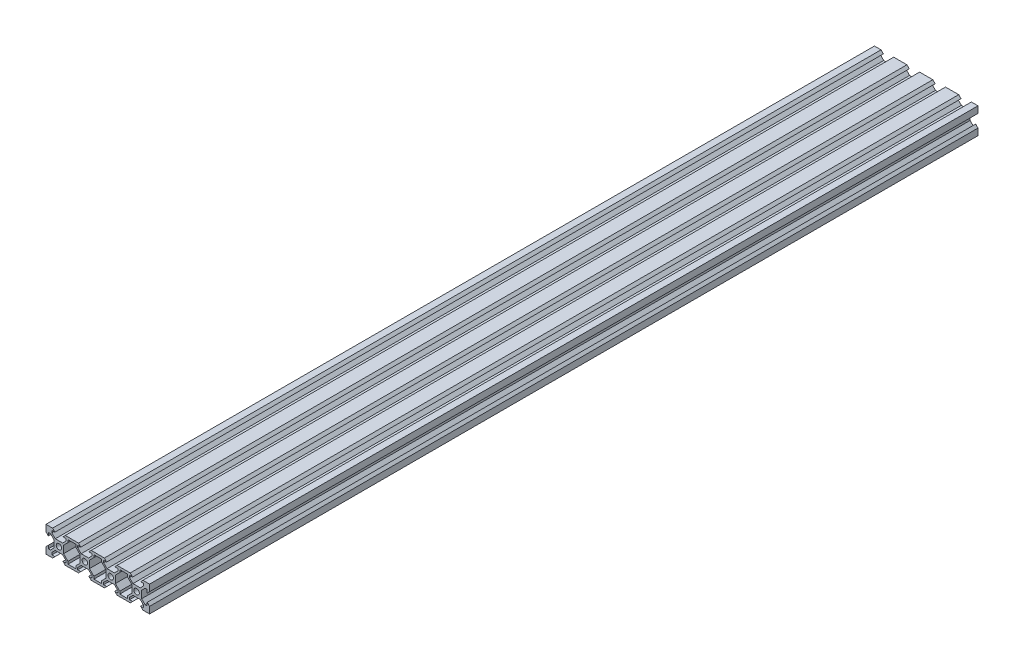
SolidWorks part; units mm, degrees
ref_plane "Plan de face" through (0, 0, 0) normal (0, 0, 1) x (1, 0, 0)
ref_plane "Plan de dessus" through (0, 0, 0) normal (0, 1, 0) x (1, 0, 0)
ref_plane "Plan de droite" through (0, 0, 0) normal (1, 0, 0) x (0, 0, -1)
sketch "Esquisse1" plane through (0, 0, 0) normal (0, 0, 1) x (1, 0, 0)
  line L45 (-65.6277, 8.2661) -> (14.3723, 8.2661)
  line L46 (-65.6277, 8.2661) -> (-65.6277, -11.7339)
  line L47 (-65.6277, -11.7339) -> (14.3723, -11.7339)
  line L48 (14.3723, 8.2661) -> (14.3723, -11.7339)
  dimension "D1" = 80
  dimension "D2" = 20
extrude "Boss.-Extru.1" add sketch "Esquisse1" along normal blind 640
sketch "Esquisse2" plane through (0, 0, 0) normal (0, 0, -1) x (-1, 0, 0)
  line L0 (-14.3723, -11.7339) -> (-14.3723, 8.2661) construction
  line L2 (50.7277, 8.2661) -> (60.5277, 8.2661)
  line L3 (-14.3723, 8.2661) -> (65.6277, 8.2661) construction
  line L4 (60.5277, 8.2661) -> (58.7277, 6.4661)
  line L5 (58.7277, 6.4661) -> (61.1277, 6.4661)
  line L6 (61.1277, 6.4661) -> (61.1277, 4.8261)
  line L7 (61.1277, 4.8261) -> (58.4677, 2.1661)
  line L8 (58.4677, 2.1661) -> (52.7877, 2.1661)
  line L9 (52.7877, 2.1661) -> (50.1277, 4.8261)
  line L10 (50.1277, 4.8261) -> (50.1277, 6.4661)
  line L11 (50.1277, 6.4661) -> (52.5277, 6.4661)
  line L12 (52.5277, 6.4661) -> (50.7277, 8.2661)
  line L43 (65.6277, 8.2661) -> (65.6277, -11.7339) construction
  line L44 (65.6277, 3.1661) -> (65.6277, -6.6339)
  line L45 (65.6277, -6.6339) -> (63.8277, -4.8339)
  line L46 (63.8277, -4.8339) -> (63.8277, -7.2339)
  line L47 (63.8277, -7.2339) -> (62.1877, -7.2339)
  line L48 (62.1877, -7.2339) -> (59.5277, -4.5739)
  line L49 (59.5277, -4.5739) -> (59.5277, 1.1061)
  line L50 (59.5277, 1.1061) -> (62.1877, 3.7661)
  line L51 (62.1877, 3.7661) -> (63.8277, 3.7661)
  line L52 (63.8277, 3.7661) -> (63.8277, 1.3661)
  line L53 (63.8277, 1.3661) -> (65.6277, 3.1661)
  line L54 (60.5277, -11.7339) -> (50.7277, -11.7339)
  line L55 (50.7277, -11.7339) -> (52.5277, -9.9339)
  line L56 (52.5277, -9.9339) -> (50.1277, -9.9339)
  line L57 (50.1277, -9.9339) -> (50.1277, -8.2939)
  line L58 (50.1277, -8.2939) -> (52.7877, -5.6339)
  line L59 (52.7877, -5.6339) -> (58.4677, -5.6339)
  line L60 (58.4677, -5.6339) -> (61.1277, -8.2939)
  line L61 (61.1277, -8.2939) -> (61.1277, -9.9339)
  line L62 (61.1277, -9.9339) -> (58.7277, -9.9339)
  line L63 (58.7277, -9.9339) -> (60.5277, -11.7339)
  line L64 (55.6277, -1.7339) -> (58.4677, 2.1661) construction
  line L65 (55.6277, -1.7339) -> (59.5277, -4.5739) construction
  line L66 (30.7277, 8.2661) -> (40.5277, 8.2661)
  line L67 (40.5277, 8.2661) -> (38.7277, 6.4661)
  line L68 (38.7277, 6.4661) -> (41.1277, 6.4661)
  line L69 (41.1277, 6.4661) -> (41.1277, 4.8261)
  line L70 (41.1277, 4.8261) -> (38.4677, 2.1661)
  line L71 (38.4677, 2.1661) -> (32.7877, 2.1661)
  line L72 (32.7877, 2.1661) -> (30.1277, 4.8261)
  line L73 (30.1277, 4.8261) -> (30.1277, 6.4661)
  line L74 (30.1277, 6.4661) -> (32.5277, 6.4661)
  line L75 (32.5277, 6.4661) -> (30.7277, 8.2661)
  line L76 (40.5277, -11.7339) -> (30.7277, -11.7339)
  line L77 (30.7277, -11.7339) -> (32.5277, -9.9339)
  line L78 (32.5277, -9.9339) -> (30.1277, -9.9339)
  line L79 (30.1277, -9.9339) -> (30.1277, -8.2939)
  line L80 (30.1277, -8.2939) -> (32.7877, -5.6339)
  line L81 (32.7877, -5.6339) -> (38.4677, -5.6339)
  line L82 (38.4677, -5.6339) -> (41.1277, -8.2939)
  line L83 (41.1277, -8.2939) -> (41.1277, -9.9339)
  line L84 (41.1277, -9.9339) -> (38.7277, -9.9339)
  line L85 (38.7277, -9.9339) -> (40.5277, -11.7339)
  line L86 (35.6277, -1.7339) -> (38.4677, 2.1661) construction
  line L87 (10.7277, 8.2661) -> (20.5277, 8.2661)
  line L88 (20.5277, 8.2661) -> (18.7277, 6.4661)
  line L89 (18.7277, 6.4661) -> (21.1277, 6.4661)
  line L90 (21.1277, 6.4661) -> (21.1277, 4.8261)
  line L91 (21.1277, 4.8261) -> (18.4677, 2.1661)
  line L92 (18.4677, 2.1661) -> (12.7877, 2.1661)
  line L93 (12.7877, 2.1661) -> (10.1277, 4.8261)
  line L94 (10.1277, 4.8261) -> (10.1277, 6.4661)
  line L95 (10.1277, 6.4661) -> (12.5277, 6.4661)
  line L96 (12.5277, 6.4661) -> (10.7277, 8.2661)
  line L97 (20.5277, -11.7339) -> (10.7277, -11.7339)
  line L98 (10.7277, -11.7339) -> (12.5277, -9.9339)
  line L99 (12.5277, -9.9339) -> (10.1277, -9.9339)
  line L100 (10.1277, -9.9339) -> (10.1277, -8.2939)
  line L101 (10.1277, -8.2939) -> (12.7877, -5.6339)
  line L102 (12.7877, -5.6339) -> (18.4677, -5.6339)
  line L103 (18.4677, -5.6339) -> (21.1277, -8.2939)
  line L104 (21.1277, -8.2939) -> (21.1277, -9.9339)
  line L105 (21.1277, -9.9339) -> (18.7277, -9.9339)
  line L106 (18.7277, -9.9339) -> (20.5277, -11.7339)
  line L107 (15.6277, -1.7339) -> (18.4677, 2.1661) construction
  line L108 (-9.2723, 8.2661) -> (0.5277, 8.2661)
  line L109 (0.5277, 8.2661) -> (-1.2723, 6.4661)
  line L110 (-1.2723, 6.4661) -> (1.1277, 6.4661)
  line L111 (1.1277, 6.4661) -> (1.1277, 4.8261)
  line L112 (1.1277, 4.8261) -> (-1.5323, 2.1661)
  line L113 (-1.5323, 2.1661) -> (-7.2123, 2.1661)
  line L114 (-7.2123, 2.1661) -> (-9.8723, 4.8261)
  line L115 (-9.8723, 4.8261) -> (-9.8723, 6.4661)
  line L116 (-9.8723, 6.4661) -> (-7.4723, 6.4661)
  line L117 (-7.4723, 6.4661) -> (-9.2723, 8.2661)
  line L118 (0.5277, -11.7339) -> (-9.2723, -11.7339)
  line L119 (-9.2723, -11.7339) -> (-7.4723, -9.9339)
  line L120 (-7.4723, -9.9339) -> (-9.8723, -9.9339)
  line L121 (-9.8723, -9.9339) -> (-9.8723, -8.2939)
  line L122 (-9.8723, -8.2939) -> (-7.2123, -5.6339)
  line L123 (-7.2123, -5.6339) -> (-1.5323, -5.6339)
  line L124 (-1.5323, -5.6339) -> (1.1277, -8.2939)
  line L125 (1.1277, -8.2939) -> (1.1277, -9.9339)
  line L126 (1.1277, -9.9339) -> (-1.2723, -9.9339)
  line L127 (-1.2723, -9.9339) -> (0.5277, -11.7339)
  line L128 (-4.3723, -1.7339) -> (-1.5323, 2.1661) construction
  line L129 (-14.3723, -6.6339) -> (-14.3723, 3.1661)
  line L130 (-14.3723, 3.1661) -> (-12.5723, 1.3661)
  line L131 (-12.5723, 1.3661) -> (-12.5723, 3.7661)
  line L132 (-12.5723, 3.7661) -> (-10.9323, 3.7661)
  line L133 (-10.9323, 3.7661) -> (-8.2723, 1.1061)
  line L134 (-8.2723, 1.1061) -> (-8.2723, -4.5739)
  line L135 (-8.2723, -4.5739) -> (-10.9323, -7.2339)
  line L136 (-10.9323, -7.2339) -> (-12.5723, -7.2339)
  line L137 (-12.5723, -7.2339) -> (-12.5723, -4.8339)
  line L138 (-12.5723, -4.8339) -> (-14.3723, -6.6339)
  line L139 (-4.3723, -1.7339) -> (-1.5323, 2.1661) construction
  line L140 (-4.3723, -1.7339) -> (-8.2723, 1.1061) construction
  circle A0 centre (55.6277, -1.7339) radius 2.1
  circle A1 centre (35.6277, -1.7339) radius 2.1
  circle A2 centre (15.6277, -1.7339) radius 2.1
  circle A3 centre (-4.3723, -1.7339) radius 2.1
  point P5 (-14.3723, -1.7339)
  point P17 (55.6277, 2.1661)
  point P54 (10.6277, 13.2661)
  dimension "D1" = 4.2
  dimension "D2" = 135
  dimension "D3" = 1.64
  dimension "D4" = 5.68
  dimension "D5" = 1.8
  dimension "D6" = 6.2
  dimension "D7" = 11
  dimension "D8" = 10
  dimension "D10" = 90
  dimension "D13" = 90
  dimension "D11" = 4
  dimension "D9" = 3
  dimension "D12" = 2
extrude "Enlèv. mat.-Extru.1" cut sketch "Esquisse2" against normal up to next
sketch "Esquisse3" plane through (0, 0, 0) normal (0, 0, -1) x (-1, 0, 0)
  line L0 (2.6183, 6.4661) -> (8.6372, 6.4661)
  line L1 (8.6372, 6.4661) -> (8.6372, 4.5061)
  line L2 (8.6372, 4.5061) -> (12.0372, 1.1061)
  line L3 (12.0372, 1.1061) -> (12.0372, -4.5739)
  line L4 (12.0372, -4.5739) -> (8.6372, -7.9739)
  line L5 (8.6372, -7.9739) -> (8.6372, -9.9339)
  line L6 (8.6372, -9.9339) -> (2.6183, -9.9339)
  line L7 (2.6183, -9.9339) -> (2.6183, -7.9739)
  line L8 (2.6183, -7.9739) -> (-0.7817, -4.5739)
  line L9 (-0.7817, -4.5739) -> (-0.7817, 1.1061)
  line L10 (-0.7817, 1.1061) -> (2.6183, 4.5061)
  line L11 (2.6183, 4.5061) -> (2.6183, 6.4661)
  line L12 (0.5277, 8.2661) -> (10.7277, 8.2661) construction
  line L13 (-1.2723, -9.9339) -> (1.1277, -9.9339) construction
  line L14 (1.1277, 6.4661) -> (-1.2723, 6.4661) construction
  line L15 (22.6183, 6.4661) -> (28.6372, 6.4661)
  line L16 (28.6372, 6.4661) -> (28.6372, 4.5061)
  line L17 (28.6372, 4.5061) -> (32.0372, 1.1061)
  line L18 (32.0372, 1.1061) -> (32.0372, -4.5739)
  line L19 (32.0372, -4.5739) -> (28.6372, -7.9739)
  line L20 (28.6372, -7.9739) -> (28.6372, -9.9339)
  line L21 (28.6372, -9.9339) -> (22.6183, -9.9339)
  line L22 (22.6183, -9.9339) -> (22.6183, -7.9739)
  line L23 (22.6183, -7.9739) -> (19.2183, -4.5739)
  line L24 (19.2183, -4.5739) -> (19.2183, 1.1061)
  line L25 (19.2183, 1.1061) -> (22.6183, 4.5061)
  line L26 (22.6183, 4.5061) -> (22.6183, 6.4661)
  line L27 (42.6183, 6.4661) -> (48.6372, 6.4661)
  line L28 (48.6372, 6.4661) -> (48.6372, 4.5061)
  line L29 (48.6372, 4.5061) -> (52.0372, 1.1061)
  line L30 (52.0372, 1.1061) -> (52.0372, -4.5739)
  line L31 (52.0372, -4.5739) -> (48.6372, -7.9739)
  line L32 (48.6372, -7.9739) -> (48.6372, -9.9339)
  line L33 (48.6372, -9.9339) -> (42.6183, -9.9339)
  line L34 (42.6183, -9.9339) -> (42.6183, -7.9739)
  line L35 (42.6183, -7.9739) -> (39.2183, -4.5739)
  line L36 (39.2183, -4.5739) -> (39.2183, 1.1061)
  line L37 (39.2183, 1.1061) -> (42.6183, 4.5061)
  line L38 (42.6183, 4.5061) -> (42.6183, 6.4661)
  circle A0 centre (-4.3723, -1.7339) radius 2.1 construction
  circle A1 centre (-4.3723, -1.7339) radius 2.1 construction
  point P13 (5.6277, 6.4661)
  point P16 (5.6277, 8.2661)
  point P28 (-0.7817, -1.7339)
  point P29 (12.0372, -1.7339)
  dimension "D1" = 5.68
  dimension "D2" = 1.96
  dimension "D3" = 3
extrude "Enlèv. mat.-Extru.2" cut sketch "Esquisse3" against normal up to next
